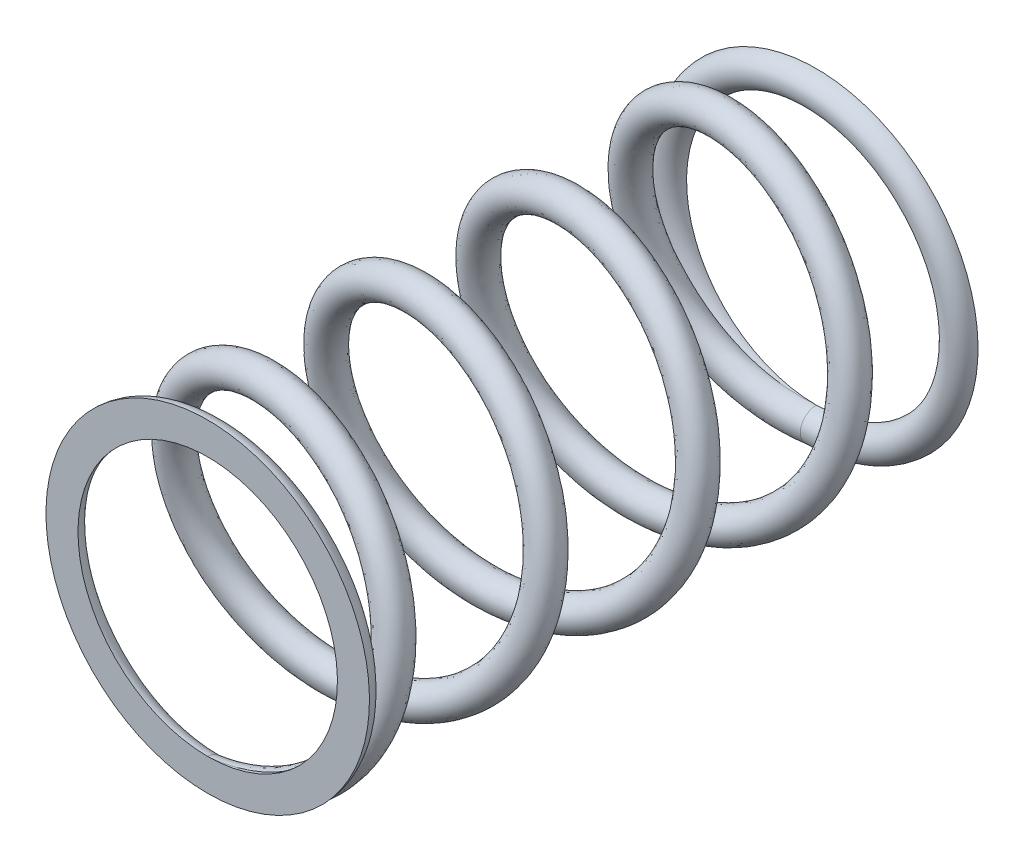
SolidWorks part; units mm, degrees
ref_plane "Piano frontale" through (0, 0, 0) normal (0, 0, 1) x (1, 0, 0)
ref_plane "Piano superiore" through (0, 0, 0) normal (0, 1, 0) x (1, 0, 0)
ref_plane "Piano destro" through (0, 0, 0) normal (1, 0, 0) x (0, 0, -1)
sketch "Schizzo1" plane through (0, 0, 0) normal (0, 0, 1) x (1, 0, 0)
  circle A0 centre (0, 0) radius 4.55
  dimension "D1" = 9.1
curve "Elica/Spirale1" pitch 4.75 height 19 turns 4
sketch "Schizzo19" plane through (0, 0, 0) normal (1, 0, 0) x (0, 0, -1)
  line L0 (0, -4.55) -> (0, 0) construction
  circle A0 centre (0, -4.55) radius 0.5
  spline S0 degree 3 poles (0, -4.55) (-0.0983, -4.55) (-0.2972, -4.3131) (-0.5937, -3.3011) (-0.8906, -1.7865) (-1.1875, 0) (-1.4844, 1.7865) (-1.7812, 3.3011) (-2.0781, 4.3131) (-2.375, 4.6685) (-2.6719, 4.3131) (-2.9687, 3.3011) (-3.3646, 1.2817) (-3.7604, -1.2817) (-4.1562, -3.3011) (-4.4531, -4.3131) (-4.75, -4.6685) (-5.0469, -4.3131) (-5.3437, -3.3011) (-5.7396, -1.2817) (-6.1354, 1.2817) (-6.5313, 3.3011) (-6.8281, 4.3131) (-7.125, 4.6685) (-7.4219, 4.3131) (-7.7188, 3.3011) (-8.1146, 1.2817) (-8.5104, -1.2817) (-8.9063, -3.3011) (-9.2031, -4.3131) (-9.5, -4.6685) (-9.7969, -4.3131) (-10.0938, -3.3011) (-10.4896, -1.2817) (-10.8854, 1.2817) (-11.2813, 3.3011) (-11.5781, 4.3131) (-11.875, 4.6685) (-12.1719, 4.3131) (-12.4688, 3.3011) (-12.8646, 1.2817) (-13.2604, -1.2817) (-13.6563, -3.3011) (-13.9531, -4.3131) (-14.25, -4.6685) (-14.5469, -4.3131) (-14.8438, -3.3011) (-15.2396, -1.2817) (-15.6354, 1.2817) (-16.0313, 3.3011) (-16.3281, 4.3131) (-16.625, 4.6685) (-16.9219, 4.3131) (-17.2188, 3.3011) (-17.5156, 1.7865) (-17.8125, 0) (-18.1094, -1.7865) (-18.4063, -3.3011) (-18.7028, -4.3131) (-18.9017, -4.55) (-19, -4.55) knots 0 0 0 0 0.015625 0.03125 0.046875 0.0625 0.078125 0.09375 0.109375 0.125 0.140625 0.15625 0.171875 0.203125 0.21875 0.234375 0.25 0.265625 0.28125 0.296875 0.328125 0.34375 0.359375 0.375 0.390625 0.40625 0.421875 0.453125 0.46875 0.484375 0.5 0.515625 0.53125 0.546875 0.578125 0.59375 0.609375 0.625 0.640625 0.65625 0.671875 0.703125 0.71875 0.734375 0.75 0.765625 0.78125 0.796875 0.828125 0.84375 0.859375 0.875 0.890625 0.90625 0.921875 0.9375 0.953125 0.96875 0.984375 1 1 1 1 construction
  dimension "D1" = 1
sweep "Sweep1" add profiles "Schizzo19" path "Elica/Spirale1"
sketch "Schizzo8" plane through (0, 0, 0) normal (0, 1, 0) x (1, 0, 0)
  line L0 (0, 0) -> (0, -17.2452) construction
sketch "Schizzo17" plane through (0, 0, 0) normal (-1, 0, 0) x (0, 0, 1)
  line L0 (-1000, 0) -> (49000, 0) construction
  circle A1 centre (19, -4.55) radius 0.5
  circle A2 centre (19, -4.55) radius 0.5
  dimension "D1" = 0
revolve "Rivoluzione3" add sketch "Schizzo17" angle 360 about L0
sketch "Schizzo18" plane through (0, 0, 0) normal (1, 0, 0) x (0, 0, -1)
  line L0 (-1000, 0) -> (49000, 0) construction
  circle A1 centre (0, -4.55) radius 0.5
  circle A2 centre (0, -4.55) radius 0.5
  dimension "D1" = 0
revolve "Rivoluzione4" add sketch "Schizzo18" angle 360 about L0
sketch "Schizzo23" plane through (0, 0, 0) normal (0, 1, 0) x (1, 0, 0)
  line L0 (4.55, 0.5) -> (-4.55, 0.5) construction
  line L1 (-5.05, 0) -> (5.05, 0)
  line L2 (-5.05, 0) -> (-5.05, 0.5)
  line L3 (-5.05, 0.5) -> (5.05, 0.5)
  line L4 (5.05, 0) -> (5.05, 0.5)
  line L5 (-5.05, 0) -> (5.05, 0.5) construction
  line L6 (-5.05, 0.5) -> (5.05, 0) construction
  line L7 (-4.55, -19.5) -> (4.55, -19.5) construction
  line L8 (5.05, -19) -> (-5.05, -19)
  line L9 (5.05, -19) -> (5.05, -19.5)
  line L10 (5.05, -19.5) -> (-5.05, -19.5)
  line L11 (-5.05, -19) -> (-5.05, -19.5)
  line L12 (5.05, -19) -> (-5.05, -19.5) construction
  line L13 (5.05, -19.5) -> (-5.05, -19) construction
  arc A0 (-4.55, 0.5) -> (-4.55, -0.5) centre (-4.55, 0) ccw construction
  arc A1 (4.55, -0.5) -> (4.55, 0.5) centre (4.55, 0) ccw construction
  arc A2 (4.55, -19.5) -> (4.55, -18.5) centre (4.55, -19) ccw construction
  arc A3 (-4.55, -18.5) -> (-4.55, -19.5) centre (-4.55, -19) ccw construction
  point P4 (0, 0.25)
  point P19 (0, -19.25)
extrude "Taglio-Estrusione1" cut sketch "Schizzo23" against normal through all both and the other way through all
